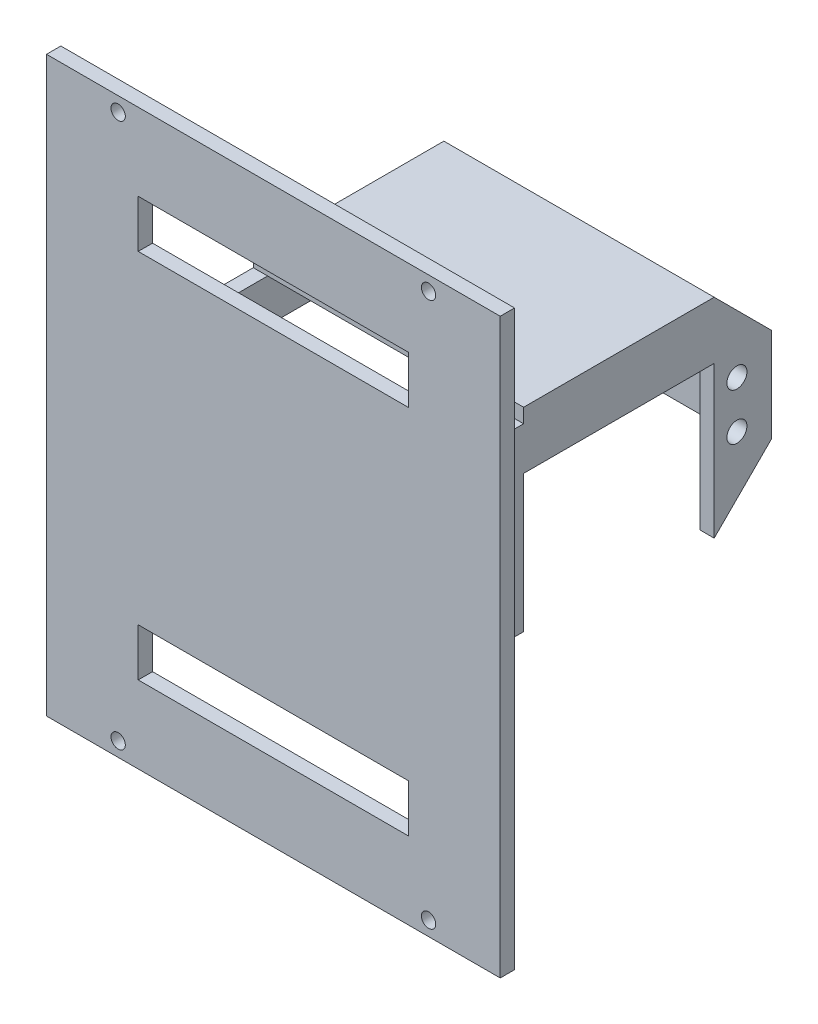
SolidWorks part; units mm, degrees
ref_plane "前视基准面" through (0, 0, 0) normal (0, 0, 1) x (1, 0, 0)
ref_plane "上视基准面" through (0, 0, 0) normal (0, 1, 0) x (1, 0, 0)
ref_plane "右视基准面" through (0, 0, 0) normal (1, 0, 0) x (0, 0, -1)
sketch "草图1" plane through (0, 0, 0) normal (0, 0, 1) x (1, 0, 0)
  line L1 (-90, 60.7792) -> (5, 60.7792)
  line L2 (-90, 60.7792) -> (-90, -59.2208)
  line L3 (-90, -59.2208) -> (5, -59.2208)
  line L4 (5, 60.7792) -> (5, -59.2208)
  dimension "D1" = 120
  dimension "D2" = 95
extrude "凸台-拉伸1" add sketch "草图1" along normal blind 3 contours L2 L1 L4 L3
sketch "草图2" plane through (0, 0, 0) normal (0, 0, -1) x (-1, 0, 0)
  line L0 (-5, 0.7792) -> (90, 0.7792) construction
  line L1 (-5, 60.7792) -> (-5, -59.2208) construction
  line L2 (90, 60.7792) -> (90, -59.2208) construction
  line L3 (42.5, 60.7792) -> (42.5, -59.2208) construction
  line L4 (90, 60.7792) -> (-5, 60.7792) construction
  line L5 (90, -59.2208) -> (-5, -59.2208) construction
  line L6 (14.2, -18.0708) -> (17.2, -18.0708)
  line L7 (14.2, 0.7792) -> (17.2, 0.7792)
  line L8 (14.2, -18.0708) -> (14.2, 19.6292)
  line L9 (14.2, 19.6292) -> (17.2, 19.6292)
  line L10 (17.2, -18.0708) -> (17.2, 19.6292)
  line L11 (70.8, -18.0708) -> (70.8, 19.6292)
  line L12 (70.8, 19.6292) -> (67.8, 19.6292)
  line L13 (67.8, -18.0708) -> (67.8, 19.6292)
  line L14 (70.8, -18.0708) -> (67.8, -18.0708)
  dimension "D1" = 3
  dimension "D2" = 28.3
  dimension "D3" = 18.85
extrude "凸台-拉伸2" add sketch "草图2" along normal blind 70 contours L10 L9 L8 L6 | L11 L12 L13 L14
sketch "草图3" plane through (-14.2, 0, 0) normal (1, 0, 0) x (0, 0, -1)
  line L0 (70, -18.0708) -> (0, -18.0708) construction
  line L1 (70, 19.6292) -> (12.1, 19.6292) construction
  line L2 (70, 19.6292) -> (70, -18.0708) construction
  line L3 (70, -18.0708) -> (12.1, -18.0708) construction
  line L4 (12.1, 19.6292) -> (12.1, -18.0708) construction
  line L5 (61, 19.6292) -> (70, 19.6292)
  line L6 (21.1, 10.6292) -> (61, 10.6292)
  line L7 (21.1, 10.6292) -> (21.1, -9.0708)
  line L8 (21.1, -9.0708) -> (61, -9.0708)
  line L9 (61, 10.6292) -> (61, -9.0708)
  line L10 (70, 19.6292) -> (70, 10.6292)
  line L11 (70, -9.0708) -> (70, -18.0708)
  line L12 (70, -18.0708) -> (61, -18.0708)
  circle A0 centre (16.34, 5.7042) radius 2.1
  circle A1 centre (16.34, -4.1458) radius 2.1
  circle A2 centre (65.76, -4.1458) radius 2.1
  circle A3 centre (65.76, 5.7042) radius 2.1
  arc A4 (61, 19.6292) -> (70, 10.6292) centre (61, 10.6292) cw
  arc A5 (70, -9.0708) -> (61, -18.0708) centre (61, -9.0708) cw
  point P23 (0, 0)
  dimension "D10" = 4.2
  dimension "D11" = 4.2
  dimension "D15" = 4.76
  dimension "D16" = 4.2
  dimension "D17" = 4.2
  dimension "D1" = 57.9
  dimension "D2" = 9
  dimension "D3" = 9
  dimension "D4" = 9
  dimension "D5" = 9
  dimension "D6" = 4.76
  dimension "D7" = 4.925
  dimension "D8" = 4.925
  dimension "D9" = 4.76
  dimension "D12" = 4.925
  dimension "D13" = 4.925
  dimension "D14" = 4.76
extrude "切除-拉伸1" cut sketch "草图3" against normal blind 61 contours L9 L6 L7 L8 | A1 | A3 | A2 | A0
sketch "草图4" plane through (0, 0, 3) normal (0, 0, 1) x (1, 0, 0)
  line L0 (-90, 0.7792) -> (5, 0.7792) construction
  line L1 (-90, 60.7792) -> (-75, 60.7792) construction
  line L2 (-90, 60.7792) -> (-90, 57.7792) construction
  line L3 (-90, 57.7792) -> (-75, 57.7792) construction
  line L4 (-75, 60.7792) -> (-75, 57.7792) construction
  line L5 (-90, 60.7792) -> (-90, -59.2208) construction
  line L6 (5, 60.7792) -> (5, -59.2208) construction
  line L7 (-42.5, 60.7792) -> (-42.5, -59.2208) construction
  line L8 (-90, 60.7792) -> (5, 60.7792) construction
  line L9 (-90, -59.2208) -> (5, -59.2208) construction
  circle A0 centre (-75, 57.7792) radius 1.5
  circle A1 centre (-10, 57.7792) radius 1.5
  circle A2 centre (-10, -56.2208) radius 1.5
  circle A3 centre (-75, -56.2208) radius 1.5
  dimension "D3" = 3
  dimension "D1" = 3
  dimension "D2" = 15
extrude "切除-拉伸2" cut sketch "草图4" against normal blind 10
sketch "草图5" plane through (0, 0, -70) normal (0, 0, -1) x (-1, 0, 0)
  line L1 (14.2, 10.6292) -> (70.8, 10.6292)
  line L2 (14.2, 10.6292) -> (14.2, -9.0708)
  line L3 (14.2, -9.0708) -> (70.8, -9.0708)
  line L4 (70.8, 10.6292) -> (70.8, -9.0708)
extrude "凸台-拉伸3" add sketch "草图5" along normal blind 3
sketch "草图6" plane through (0, 19.6292, 0) normal (0, 1, 0) x (1, 0, 0)
  line L0 (-14.2, 70) -> (-14.2, 0) construction
  line L1 (-70.8, 61) -> (-14.2, 61)
  line L2 (-70.8, 61) -> (-70.8, 21.1)
  line L3 (-70.8, 21.1) -> (-14.2, 21.1)
  line L4 (-14.2, 61) -> (-14.2, 21.1)
  dimension "D1" = 39.9
extrude "凸台-拉伸4" add sketch "草图6" along normal blind 3
sketch "草图8" plane through (-14.2, 0, 0) normal (1, 0, 0) x (0, 0, -1)
  line L0 (61, 22.6292) -> (61, 19.6292)
  line L1 (61, 19.6292) -> (70, 19.6292)
  line L2 (70, 19.6292) -> (70, 10.6292)
  line L3 (70, 10.6292) -> (73, 10.6292)
  line L4 (73, 10.6292) -> (73, 22.6292)
  line L5 (73, 22.6292) -> (61, 22.6292)
  line L6 (73, -9.0708) -> (70, -9.0708)
  line L7 (70, -9.0708) -> (70, -18.0708)
  line L8 (70, -18.0708) -> (61, -18.0708)
  line L9 (70, -18.0708) -> (0, -18.0708) construction
  line L10 (61, -18.0708) -> (61, -21.0708)
  line L11 (61, -21.0708) -> (73, -21.0708)
  line L12 (73, -21.0708) -> (73, -9.0708)
  dimension "D1" = 3
extrude "凸台-拉伸5" add sketch "草图8" against normal blind 3
sketch "草图9" plane through (-70.8, 0, 0) normal (-1, 0, 0) x (0, 0, 1)
  line L1 (-73, 10.6292) -> (-61, 10.6292)
  line L2 (-73, 10.6292) -> (-73, 22.6292)
  line L3 (-73, 22.6292) -> (-61, 22.6292)
  line L4 (-61, 10.6292) -> (-61, 22.6292)
  line L5 (-73, -9.0708) -> (-61, -9.0708)
  line L6 (-73, -9.0708) -> (-73, -21.0708)
  line L7 (-73, -21.0708) -> (-61, -21.0708)
  line L8 (-61, -9.0708) -> (-61, -21.0708)
extrude "凸台-拉伸6" add sketch "草图9" against normal blind 3
sketch "草图10" plane through (-14.2, 0, 0) normal (1, 0, 0) x (0, 0, -1)
  line L0 (73, 10.6292) -> (73, 22.6292)
  line L1 (73, 22.6292) -> (61, 22.6292)
  line L2 (21.1, 22.6292) -> (73, 22.6292) construction
  line L3 (61, 22.6292) -> (73, 10.6292)
  line L4 (73, -9.0708) -> (73, -21.0708)
  line L5 (73, -21.0708) -> (61, -21.0708)
  line L6 (61, -21.0708) -> (73, -9.0708)
  line L7 (61, -9.0708) -> (61, -18.0708)
  line L8 (61, -18.0708) -> (21.1, -18.0708)
  line L9 (61, -18.0708) -> (0, -18.0708) construction
  line L10 (21.1, -18.0708) -> (21.1, -9.0708)
  line L11 (21.1, -9.0708) -> (61, -9.0708)
extrude "切除-拉伸4" cut sketch "草图10" against normal blind 74
sketch "草图13" plane through (0, 0, 0) normal (0, 0, -1) x (-1, 0, 0)
  line L0 (14.2, 22.6292) -> (14.2, 60.7792) construction
  line L1 (90, 60.7792) -> (-5, 60.7792) construction
  line L2 (14.2, 60.7792) -> (70.8, 22.6292) construction
  line L3 (70.8, 22.6292) -> (70.8, 60.7792) construction
  line L4 (70.8, 60.7792) -> (14.2, 60.7792) construction
  line L5 (14.2, -21.0708) -> (14.2, -59.2208) construction
  line L6 (14.2, 44.6292) -> (70.8, 44.6292)
  line L7 (14.2, 44.6292) -> (14.2, 34.6292)
  line L8 (14.2, 34.6292) -> (70.8, 34.6292)
  line L9 (70.8, 44.6292) -> (70.8, 34.6292)
  line L10 (90, -59.2208) -> (-5, -59.2208) construction
  line L11 (14.2, -59.2208) -> (70.8, -21.0708) construction
  line L12 (70.8, -21.0708) -> (70.8, -59.2208) construction
  line L13 (17.2, 22.6292) -> (67.8, 22.6292) construction
  line L14 (14.2, -33.0708) -> (70.8, -33.0708)
  line L15 (14.2, -33.0708) -> (14.2, -43.0708)
  line L16 (14.2, -43.0708) -> (70.8, -43.0708)
  line L17 (70.8, -33.0708) -> (70.8, -43.0708)
  line L18 (17.2, -21.0708) -> (14.2, -21.0708) construction
  dimension "D1" = 12
  dimension "D2" = 12
  dimension "D3" = 10
  dimension "D4" = 10
extrude "切除-拉伸5" cut sketch "草图13" against normal blind 14
